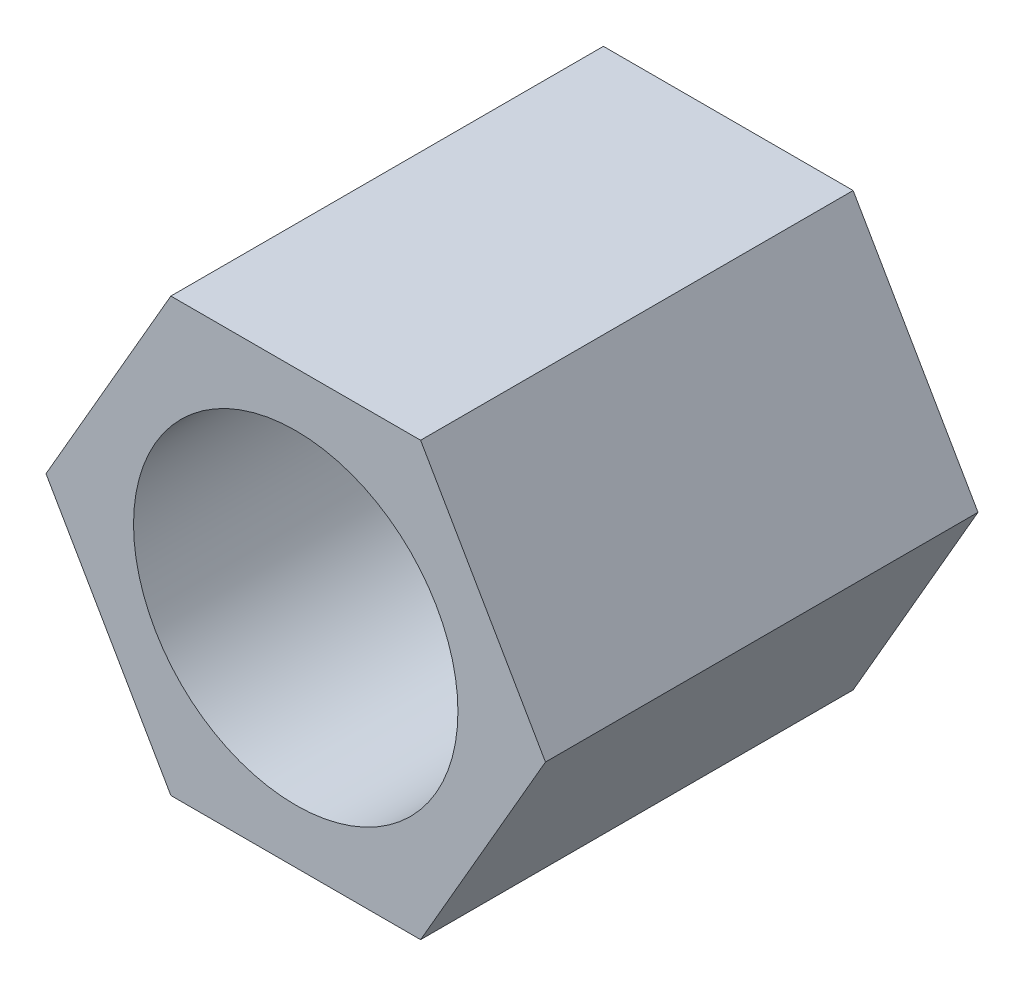
SolidWorks part; units mm, degrees
ref_plane "前视基准面" through (0, 0, 0) normal (0, 0, 1) x (1, 0, 0)
ref_plane "上视基准面" through (0, 0, 0) normal (0, 1, 0) x (1, 0, 0)
ref_plane "右视基准面" through (0, 0, 0) normal (1, 0, 0) x (0, 0, -1)
other "Configuration Table"
sketch "草图1" plane through (0, 0, 0) normal (0, 0, 1) x (1, 0, 0)
  line L1 (2.3094, 0) -> (1.1547, 2)
  line L2 (1.1547, 2) -> (-1.1547, 2)
  line L3 (-1.1547, 2) -> (-2.3094, 0)
  line L4 (-2.3094, 0) -> (-1.1547, -2)
  line L5 (-1.1547, -2) -> (1.1547, -2)
  line L6 (1.1547, -2) -> (2.3094, 0)
  circle A0 centre (0, 0) radius 2 construction
  circle A1 centre (0, 0) radius 1.5
  dimension "D1" = 2
extrude "凸台-拉伸1" add sketch "草图1" along normal blind 4
